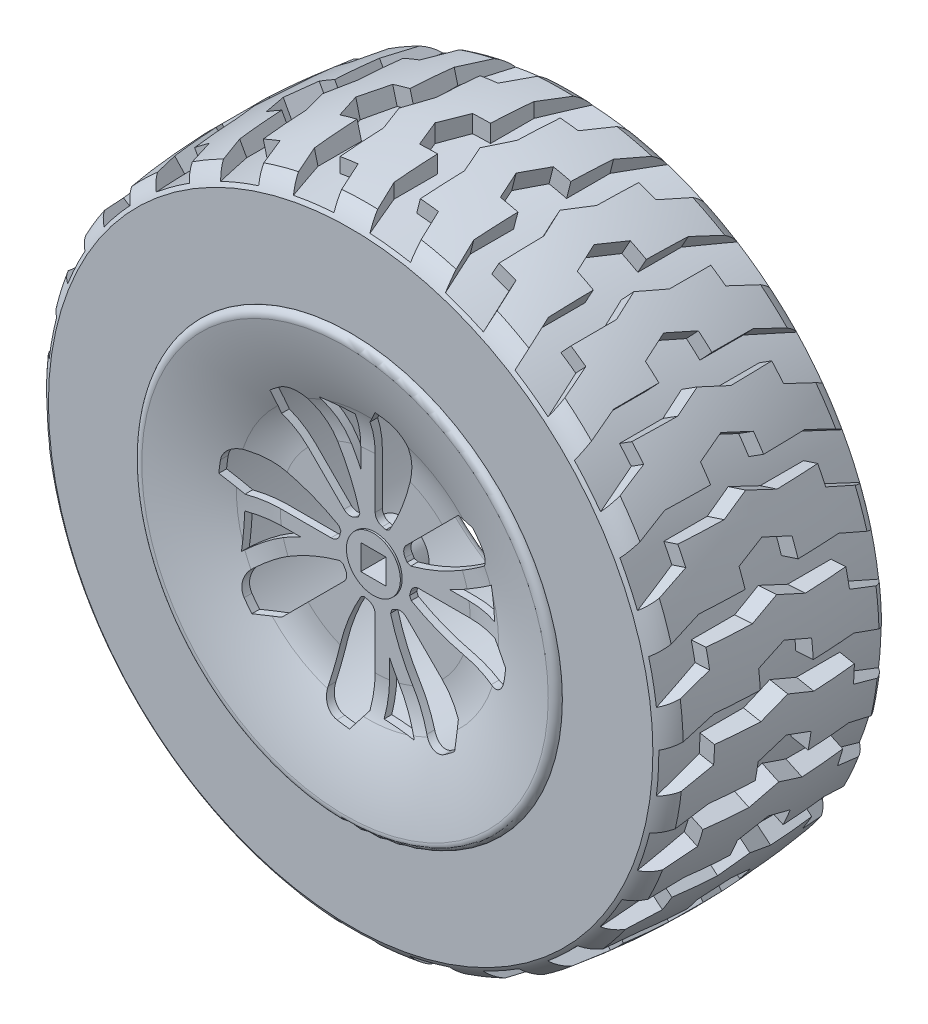
SolidWorks part; units mm, degrees
material "Rubber"
ref_plane "Front Plane" through (0, 0, 0) normal (0, 0, 1) x (1, 0, 0)
ref_plane "Top Plane" through (0, 0, 0) normal (0, 1, 0) x (1, 0, 0)
ref_plane "Right Plane" through (0, 0, 0) normal (1, 0, 0) x (0, 0, -1)
sketch "Sketch1" plane through (0, 0, 0) normal (0, 0, 1) x (1, 0, 0)
  circle A0 centre (0, 0) radius 42.5
  dimension "D1" = 85
extrude "Boss-Extrude1" add sketch "Sketch1" along normal blind 31.5
sketch "Sketch2" plane through (0, 0, 0) normal (0, 1, 0) x (1, 0, 0)
  line L0 (0, -1000) -> (0, 49000) construction
  line L1 (-1040, -15.75) -> (48960, -15.75) construction
  line L2 (-42.5, 0) -> (-42.5, -31.5) construction
  line L3 (-2.5, 0) -> (2.5, 0)
  line L4 (42.5, 0) -> (-42.5, 0) construction
  line L5 (-2.5, -31.5) -> (2.5, -31.5)
  line L6 (-2.5, -12.0711) -> (0, -12.0711)
  line L7 (0, -12.0711) -> (0, -6.0355)
  line L8 (-42.5, -31.5) -> (42.5, -31.5) construction
  line L9 (-2.5, 0) -> (-5, -6.0355)
  line L10 (-9.0239, -15.75) -> (-7.5, -19.4289)
  line L11 (2.5, 0) -> (0, -6.0355)
  line L12 (-4.0239, -15.75) -> (-2.5, -19.4289)
  line L13 (0, -19.4289) -> (0, -25.4645)
  line L14 (-2.5, -19.4289) -> (0, -19.4289)
  line L15 (0, -25.4645) -> (2.5, -31.5)
  line L16 (-2.5, -12.0711) -> (-4.0239, -15.75)
  line L17 (-5, -6.0355) -> (-7.5, -6.0355)
  line L18 (-7.5, -6.0355) -> (-7.5, -12.0711)
  line L19 (-7.5, -25.4645) -> (-7.5, -19.4289)
  line L20 (-5, -25.4645) -> (-7.5, -25.4645)
  line L21 (-7.5, -12.0711) -> (-9.0239, -15.75)
  line L22 (-5, -25.4645) -> (-2.5, -31.5)
  point P8 (-42.5, -15.75)
  point P13 (0, 0)
  point P18 (0, -31.5)
  dimension "D1" = 5
  dimension "D2" = 67.5
  dimension "D3" = 2.5
  dimension "D4" = 2.5
extrude "Boss-Extrude2" add sketch "Sketch2" along normal blind 45
ref_axis "Axis1" through (0, 0, 31.5) along (0, 0, -1)
pattern_circular "CirPattern1" count 25 over 360 about axis through (0, 0, 0) along (0, 0, 1) of "Boss-Extrude2"
sketch "Sketch4" plane through (0, 0, 0) normal (1, 0, 0) x (0, 0, -1)
  line L0 (0, 0) -> (0, 45) construction
  line L1 (0, 45) -> (-31.5, 45) construction
  line L2 (-31.5, 45) -> (-31.5, 0) construction
  line L3 (-29.75, 22.5) -> (0, 22.5) construction
  line L4 (-15.75, -954.6695) -> (-15.75, 49045.3305) construction
  line L5 (-31.5, 41.9943) -> (-31.5, 29.4312)
  line L6 (-15.75, 45) -> (-15.75, 50.3305)
  line L7 (9.25, 50.3305) -> (-40.75, 50.3305)
  line L8 (-40.75, 50.3305) -> (-40.75, 22.5)
  line L9 (-40.75, 22.5) -> (-29.75, 22.5)
  line L10 (9.25, 22.5) -> (-1.75, 22.5)
  line L11 (9.25, 50.3305) -> (9.25, 22.5)
  line L12 (0, 41.9943) -> (0, 29.4312)
  line L13 (-31.5, 0) -> (0, 0) construction
  line L14 (-31.5, 0.1689) -> (-31.5, -5.4942) construction
  line L16 (-31.5, 22.5) -> (0, 22.5)
  line L17 (-31.5, 22.5) -> (-31.5, 0)
  line L18 (-31.5, 0) -> (0, 0)
  line L19 (0, 22.5) -> (0, 0)
  arc A0 (-2.15, 44.0709) -> (0, 41.9943) centre (-4.3898, 39.6006) cw
  arc A1 (-31.5, 29.4312) -> (-29.75, 22.5) centre (14.3268, 37.3151) ccw
  arc A2 (-29.35, 44.0709) -> (-31.5, 41.9943) centre (-27.1102, 39.6006) ccw
  arc A3 (-29.35, 44.0709) -> (-2.15, 44.0709) centre (-15.75, -55) cw
  arc A4 (0, 29.4312) -> (-1.75, 22.5) centre (-45.8268, 37.3151) cw
  point P14 (-15.75, 45)
  dimension "D2" = 100
  dimension "D5" = 1.75
  dimension "D6" = 46.5
  dimension "D7" = 10
  dimension "D1" = 45
  dimension "D3" = 2.15
  dimension "D8" = 25
revolve "Cut-Revolve9" cut sketch "Sketch4" angle 360 about axis through (0, 0, 31.5) along (0, 0, -1)
sketch "Sketch6" plane through (0, 0, 0) normal (1, 0, 0) x (0, 0, -1)
  line L0 (-31.5, 41.9943) -> (-31.5, 29.4312) construction
  line L1 (0, 41.9943) -> (0, 29.4312) construction
  line L2 (-31.5, 41.9943) -> (-31.5, 29.4312) construction
  line L3 (0, 41.9943) -> (0, 29.4312) construction
  line L4 (-1.75, 37.0576) -> (-1.75, 29.5821)
  line L5 (-29.75, 37.0576) -> (-29.75, 29.5821)
  line L6 (-28.0912, 23.0576) -> (-28.0912, 20.5576)
  line L7 (-3.4088, 23.0576) -> (-3.4088, 20.5576)
  line L8 (-5.9088, 18.0576) -> (-25.5912, 18.0576)
  line L9 (-27.25, 39.5576) -> (-4.25, 39.5576)
  line L10 (-1.75, 39.5821) -> (-1.75, 29.5821) construction
  line L11 (-29.75, 39.5821) -> (-29.75, 29.5821) construction
  arc A0 (-31.5, 29.4312) -> (-29.75, 22.5) centre (14.3268, 37.3151) ccw construction
  arc A4 (-1.75, 22.5) -> (0, 29.4312) centre (-45.8268, 37.3151) ccw construction
  arc A5 (-31.5, 29.4312) -> (-29.75, 22.5) centre (14.3268, 37.3151) ccw construction
  arc A6 (-1.75, 37.0576) -> (-4.25, 39.5576) centre (-4.25, 37.0576) ccw
  arc A7 (-27.25, 39.5576) -> (-29.75, 37.0576) centre (-27.25, 37.0576) ccw
  arc A8 (-3.4088, 20.5576) -> (-5.9088, 18.0576) centre (-5.9088, 20.5576) cw
  arc A9 (-1.75, 22.5) -> (0, 29.4312) centre (-45.8268, 37.3151) ccw construction
  arc A10 (-3.4088, 23.0576) -> (-1.75, 29.5821) centre (-45.8268, 37.3151) ccw
  arc A11 (-28.0912, 20.5576) -> (-25.5912, 18.0576) centre (-25.5912, 20.5576) ccw
  arc A14 (-29.75, 29.5821) -> (-28.0912, 23.0576) centre (14.3268, 37.3151) ccw
  arc A15 (-0.9335, 41.1602) -> (-30.7168, 41.1124) centre (-15.75, -5.6543) ccw construction
  arc A16 (0, 41.9943) -> (-0.9335, 41.1602) centre (1.9968, 38.8202) ccw construction
  arc A17 (-30.7168, 41.1124) -> (-31.5, 41.9943) centre (-34.3917, 38.6376) ccw construction
  arc A18 (-1.75, 39.5821) -> (-1.75, 39.5821) centre (-1.75, 39.5821) ccw construction
  arc A19 (-1.75, 39.5821) -> (-29.75, 39.5821) centre (-15.75, -5.6543) ccw construction
  arc A20 (-29.75, 39.5821) -> (-29.75, 39.5821) centre (-29.75, 39.5821) ccw construction
  point P38 (-28.0912, 18.0576)
  dimension "D4" = 2.5
  dimension "D2" = 2.5
  dimension "D3" = 5
  dimension "D5" = 21.5
  dimension "D1" = 1.75
revolve "Cut-Revolve14" cut sketch "Sketch6" angle 360 about L18
sketch "Sketch8" plane through (0, 0, 0) normal (1, 0, 0) x (0, 0, -1)
  line L0 (-28.0912, -22.5) -> (-28.0912, 22.5) construction
  line L2 (-31.5, 29.4312) -> (-31.3022, 29.4312)
  line L3 (0, 29.4312) -> (-0.1978, 29.4312)
  line L4 (-29.75, 22.5) -> (-1.75, 22.5)
  line L5 (-27.9368, 21.5) -> (-1.75, 21.5)
  line L6 (-27.0912, 3.75) -> (-27.0912, 13.1839)
  line L7 (-31.5, 0) -> (0, 0) construction
  line L8 (-27.0912, 0) -> (-27.0912, 13.1839) construction
  line L9 (-28.0912, 3.75) -> (-28.0912, 13.1839)
  line L10 (-29.75, 21.5) -> (-1.75, 21.5) construction
  line L11 (-27.0912, 3.75) -> (-24.3412, 3.75)
  line L12 (-24.3412, 3.75) -> (-24.3412, 0)
  line L13 (-28.0912, 0) -> (-28.0912, 13.1839) construction
  line L14 (-28.0912, 3.75) -> (-28.3412, 3.75)
  line L15 (-28.3412, 3.75) -> (-28.3412, 0)
  line L16 (-28.3412, 0) -> (-24.3412, 0)
  arc A0 (-31.5, 29.4312) -> (-29.75, 22.5) centre (14.3268, 37.3151) ccw construction
  arc A1 (-28.2317, 18.6147) -> (-27.0912, 13.1839) centre (-40.5912, 13.1839) cw
  arc A2 (-1.75, 21.5) -> (-0.822, 22.1668) centre (-1.75, 22.4792) ccw
  arc A3 (-1.75, 22.5) -> (0, 29.4312) centre (-45.8268, 37.3151) ccw construction
  arc A4 (-31.5, 29.4312) -> (-29.75, 22.5) centre (14.3268, 37.3151) ccw
  arc A5 (-32.2838, 28.2401) -> (-29.1472, 18.2124) centre (14.3268, 37.3151) ccw
  arc A6 (-0.822, 22.1668) -> (0.7838, 28.2401) centre (-45.8268, 37.3151) ccw
  arc A7 (-1.75, 22.5) -> (0, 29.4312) centre (-45.8268, 37.3151) ccw
  arc A8 (-29.1472, 18.2124) -> (-28.0912, 13.1839) centre (-40.5912, 13.1839) cw
  arc A9 (0.7838, 28.2401) -> (-0.1978, 29.4312) centre (-0.1978, 28.4312) ccw
  arc A10 (-32.2838, 28.2401) -> (-31.3022, 29.4312) centre (-31.3022, 28.4312) cw
  arc A11 (-28.866, 20.1303) -> (-28.2317, 18.6147) centre (14.3268, 37.3151) ccw
  arc A12 (-31.3022, 28.4312) -> (-28.2317, 18.6147) centre (14.3268, 37.3151) ccw construction
  arc A13 (-28.866, 20.1303) -> (-27.9368, 21.5) centre (-27.9368, 20.5) cw
  point P29 (-28.0912, 15.9699)
  point P32 (1, 29.4312)
  point P35 (-32.5, 29.4312)
  dimension "D5" = 12.5
  dimension "D6" = 1
  dimension "D7" = 1
  dimension "D1" = 1
  dimension "D2" = 1
  dimension "D9" = 3.75
  dimension "D10" = 0.25
  dimension "D8" = 4
  dimension "D3" = 1
  dimension "D4" = 1
revolve "Revolve1" add sketch "Sketch8" angle 360 about axis through (0, 0, 31.5) along (0, 0, -1)
sketch "Sketch9" plane through (0, 0, 24.3412) normal (0, 0, -1) x (-1, 0, 0)
  line L0 (0, -1000) -> (0, 17.3576) construction
  line L1 (-1.75, 1.75) -> (1.75, 1.75)
  line L2 (-1.75, 1.75) -> (-1.75, -1.75)
  line L3 (-1.75, -1.75) -> (1.75, -1.75)
  line L4 (1.75, 1.75) -> (1.75, -1.75)
  line L5 (-1.75, 1.75) -> (1.75, -1.75) construction
  line L6 (-1.75, -1.75) -> (1.75, 1.75) construction
  line L7 (0, 6.1237) -> (0, 17.3576)
  line L8 (-1.9889, 5.01) -> (-1.4961, 4.7709)
  line L9 (-1.7657, 19.9219) -> (0, 17.3576)
  line L10 (-4.3301, 4.3301) -> (-12.2737, 12.2737)
  line L11 (-4.949, 2.1362) -> (-4.4315, 2.3156)
  line L12 (-15.3355, 12.8384) -> (-12.2737, 12.2737)
  line L13 (-6.1237, 0) -> (-17.3576, 0)
  line L14 (-5.01, -1.9889) -> (-4.7709, -1.4961)
  line L15 (-19.9219, -1.7657) -> (-17.3576, 0)
  line L16 (-4.3301, -4.3301) -> (-12.2737, -12.2737)
  line L17 (-2.1362, -4.949) -> (-2.3156, -4.4315)
  line L18 (-12.8384, -15.3355) -> (-12.2737, -12.2737)
  line L19 (0, -6.1237) -> (0, -17.3576)
  line L20 (1.9889, -5.01) -> (1.4961, -4.7709)
  line L21 (1.7657, -19.9219) -> (0, -17.3576)
  line L22 (4.3301, -4.3301) -> (12.2737, -12.2737)
  line L23 (4.949, -2.1362) -> (4.4315, -2.3156)
  line L24 (15.3355, -12.8384) -> (12.2737, -12.2737)
  line L25 (6.1237, 0) -> (17.3576, 0)
  line L26 (5.01, 1.9889) -> (4.7709, 1.4961)
  line L27 (19.9219, 1.7657) -> (17.3576, 0)
  line L28 (4.3301, 4.3301) -> (12.2737, 12.2737)
  line L29 (2.1362, 4.949) -> (2.3156, 4.4315)
  line L30 (12.8384, 15.3355) -> (12.2737, 12.2737)
  line L31 (2, 10.3436) -> (2, 17.3576)
  line L32 (2, 17.3576) -> (6.6552, 17.3576)
  line L33 (2, 6.1237) -> (2, 17.3576) construction
  line L34 (10.3436, -2) -> (17.3576, -2)
  line L35 (17.3576, -2) -> (17.3576, -6.6552)
  line L36 (-2, -10.3436) -> (-2, -17.3576)
  line L37 (-2, -17.3576) -> (-6.6552, -17.3576)
  line L38 (-10.3436, 2) -> (-17.3576, 2)
  line L39 (-17.3576, 2) -> (-17.3576, 6.6552)
  circle A0 centre (0, 0) radius 21.5 construction
  circle A1 centre (0, 0) radius 21.5 construction
  arc A2 (-1, 4.899) -> (-1.4961, 4.7709) centre (0, 0) ccw
  arc A3 (-1.7657, 19.9219) -> (-3.5138, 19.6889) centre (0, 0) ccw
  arc A4 (-1.9889, 5.01) -> (-5.5708, 17.0899) centre (21.6625, 18.5939) cw
  arc A5 (-5.5708, 17.0899) -> (-3.5138, 19.6889) centre (-3.0746, 17.2278) cw
  arc A6 (0, 6.1237) -> (-1, 4.899) centre (-1.25, 6.1237) cw
  arc A7 (-4.1712, 2.757) -> (-4.4315, 2.3156) centre (0, 0) ccw
  arc A8 (-15.3355, 12.8384) -> (-16.4068, 11.4375) centre (0, 0) ccw
  arc A9 (-4.949, 2.1362) -> (-16.0235, 8.1453) centre (2.1698, 28.4656) cw
  arc A10 (-16.0235, 8.1453) -> (-16.4068, 11.4375) centre (-14.3559, 10.0078) cw
  arc A11 (-4.3301, 4.3301) -> (-4.1712, 2.757) centre (-5.214, 3.4462) cw
  arc A12 (-4.899, -1) -> (-4.7709, -1.4961) centre (0, 0) ccw
  arc A13 (-19.9219, -1.7657) -> (-19.6889, -3.5138) centre (0, 0) ccw
  arc A14 (-5.01, -1.9889) -> (-17.0899, -5.5708) centre (-18.5939, 21.6625) cw
  arc A15 (-17.0899, -5.5708) -> (-19.6889, -3.5138) centre (-17.2278, -3.0746) cw
  arc A16 (-6.1237, 0) -> (-4.899, -1) centre (-6.1237, -1.25) cw
  arc A17 (-2.757, -4.1712) -> (-2.3156, -4.4315) centre (0, 0) ccw
  arc A18 (-12.8384, -15.3355) -> (-11.4375, -16.4068) centre (0, 0) ccw
  arc A19 (-2.1362, -4.949) -> (-8.1453, -16.0235) centre (-28.4656, 2.1698) cw
  arc A20 (-8.1453, -16.0235) -> (-11.4375, -16.4068) centre (-10.0078, -14.3559) cw
  arc A21 (-4.3301, -4.3301) -> (-2.757, -4.1712) centre (-3.4462, -5.214) cw
  arc A22 (1, -4.899) -> (1.4961, -4.7709) centre (0, 0) ccw
  arc A23 (1.7657, -19.9219) -> (3.5138, -19.6889) centre (0, 0) ccw
  arc A24 (1.9889, -5.01) -> (5.5708, -17.0899) centre (-21.6625, -18.5939) cw
  arc A25 (5.5708, -17.0899) -> (3.5138, -19.6889) centre (3.0746, -17.2278) cw
  arc A26 (0, -6.1237) -> (1, -4.899) centre (1.25, -6.1237) cw
  arc A27 (4.1712, -2.757) -> (4.4315, -2.3156) centre (0, 0) ccw
  arc A28 (15.3355, -12.8384) -> (16.4068, -11.4375) centre (0, 0) ccw
  arc A29 (4.949, -2.1362) -> (16.0235, -8.1453) centre (-2.1698, -28.4656) cw
  arc A30 (16.0235, -8.1453) -> (16.4068, -11.4375) centre (14.3559, -10.0078) cw
  arc A31 (4.3301, -4.3301) -> (4.1712, -2.757) centre (5.214, -3.4462) cw
  arc A32 (4.899, 1) -> (4.7709, 1.4961) centre (0, 0) ccw
  arc A33 (19.9219, 1.7657) -> (19.6889, 3.5138) centre (0, 0) ccw
  arc A34 (5.01, 1.9889) -> (17.0899, 5.5708) centre (18.5939, -21.6625) cw
  arc A35 (17.0899, 5.5708) -> (19.6889, 3.5138) centre (17.2278, 3.0746) cw
  arc A36 (6.1237, 0) -> (4.899, 1) centre (6.1237, 1.25) cw
  arc A37 (2.757, 4.1712) -> (2.3156, 4.4315) centre (0, 0) ccw
  arc A38 (12.8384, 15.3355) -> (11.4375, 16.4068) centre (0, 0) ccw
  arc A39 (2.1362, 4.949) -> (8.1453, 16.0235) centre (28.4656, -2.1698) cw
  arc A40 (8.1453, 16.0235) -> (11.4375, 16.4068) centre (10.0078, 14.3559) cw
  arc A41 (4.3301, 4.3301) -> (2.757, 4.1712) centre (3.4462, 5.214) cw
  arc A42 (0.2056, 5.471) -> (6.6552, 17.3576) centre (28.4656, -2.1698) cw construction
  arc A43 (2, 10.3436) -> (6.6552, 17.3576) centre (28.4656, -2.1698) cw
  arc A44 (10.3436, -2) -> (17.3576, -6.6552) centre (-2.1698, -28.4656) cw
  arc A45 (-2, -10.3436) -> (-6.6552, -17.3576) centre (-28.4656, 2.1698) cw
  arc A46 (-10.3436, 2) -> (-17.3576, 6.6552) centre (2.1698, 28.4656) cw
  point P18 (0, 5)
  point P99 (0, 0)
  point P118 (0, 0)
  dimension "D2" = 10
  dimension "D3" = 40
  dimension "D4" = 2.5
  dimension "D5" = 1.25
  dimension "D9" = 4
  dimension "D1" = 3.5
  dimension "D6" = 8
  dimension "D7" = 2
  dimension "D8" = 2
extrude "Cut-Extrude1" cut sketch "Sketch9" against normal through all
equation "\"D4@Sketch2\"=\"D3@Sketch2\""
equation "\"D2@Sketch8\"=\"D1@Sketch8\""
equation "\"D4@Sketch8\"=\"D3@Sketch8\""
